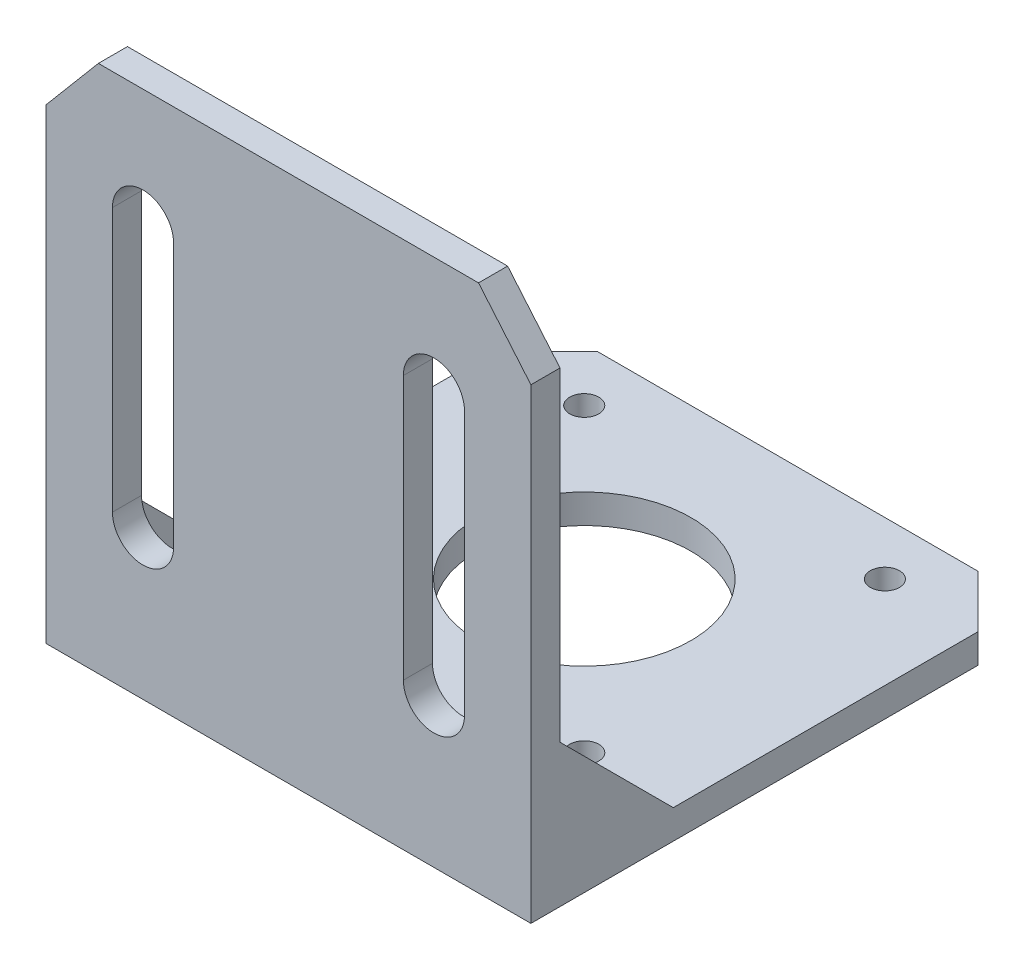
SolidWorks part; units mm, degrees
ref_plane "前视基准面" through (0, 0, 0) normal (0, 0, 1) x (1, 0, 0)
ref_plane "上视基准面" through (0, 0, 0) normal (0, 1, 0) x (1, 0, 0)
ref_plane "右视基准面" through (0, 0, 0) normal (1, 0, 0) x (0, 0, -1)
other "Configuration Table"
sketch "草图1" plane through (0, 0, 0) normal (0, 1, 0) x (1, 0, 0)
  line L0 (0, 32.108) -> (0, -16.3383) construction
  line L1 (-25, -23.05) -> (25, -23.05)
  line L2 (-25, -23.05) -> (-25, 23.05)
  line L3 (-19.6, 28.45) -> (19.6, 28.45)
  line L4 (25, -23.05) -> (25, 23.05)
  line L7 (-19.6, 28.45) -> (-25, 23.05)
  line L8 (19.6, 28.45) -> (25, 23.05)
  circle A1 centre (-15.5, 22.95) radius 1.5
  circle A2 centre (15.5, 22.95) radius 1.5
  circle A3 centre (-15.5, -8.05) radius 1.5
  circle A4 centre (15.5, -8.05) radius 1.5
  circle A5 centre (0, 7.45) radius 11
  point P0 (0, 0)
  dimension "D1" = 22
  dimension "D4" = 3
  dimension "D5" = 15.5
  dimension "D9" = 21
  dimension "D10" = 5.5
  dimension "D11" = 31
  dimension "D2" = 5.4
  dimension "D3" = 5.4
  dimension "D7" = 50
  dimension "D8" = 51.5
  dimension "D6" = 2
extrude "凸台-拉伸1" add sketch "草图1" along normal blind 3
ref_plane "基准面1" through (0, 0, 23.05) normal (0, 0, 1) x (1, 0, 0)
sketch "草图3" plane through (0, 0, 23.05) normal (0, 0, 1) x (1, 0, 0)
  line L0 (25, 0) -> (-25, 0)
  line L1 (-25, 0) -> (-25, 48.1)
  line L2 (-19.6, 54.5) -> (19.6, 54.5)
  line L3 (25, 48.1) -> (25, 0)
  line L4 (0, 60.86) -> (0, 19.2653) construction
  line L5 (-15, 42.35) -> (-15, 15.15) construction
  line L6 (-11.85, 42.35) -> (-11.85, 15.15)
  line L7 (-18.15, 42.35) -> (-18.15, 15.15)
  line L8 (15, 42.35) -> (15, 15.15) construction
  line L9 (11.85, 42.35) -> (11.85, 15.15)
  line L10 (18.15, 42.35) -> (18.15, 15.15)
  line L11 (-25, 48.1) -> (-19.6, 54.5)
  line L12 (25, 48.1) -> (19.6, 54.5)
  arc A0 (-11.85, 42.35) -> (-18.15, 42.35) centre (-15, 42.35) ccw
  arc A1 (-18.15, 15.15) -> (-11.85, 15.15) centre (-15, 15.15) ccw
  arc A2 (11.85, 42.35) -> (18.15, 42.35) centre (15, 42.35) cw
  arc A3 (18.15, 15.15) -> (11.85, 15.15) centre (15, 15.15) cw
  point P11 (-15, 28.75)
  point P16 (-15, 45.5)
  point P17 (-15, 12)
  point P20 (15, 28.75)
  dimension "D4" = 9
  dimension "D1" = 6.3
  dimension "D2" = 33.5
  dimension "D3" = 15
extrude "凸台-拉伸2" add sketch "草图3" against normal blind 3
sketch "草图4" plane through (-25, 0, 0) normal (-1, 0, 0) x (0, 0, 1)
  line L0 (20.05, 14.6802) -> (8.3698, 3)
  line L1 (20.05, 48.1) -> (20.05, 3) construction
  line L2 (-23.05, 3) -> (20.05, 3) construction
  dimension "D1" = 45
rib "筋2" sketch "草图4" sketch "草图4" thickness 3 extrusion direction parallel to sketch draft on no parameters "D1"=3
mirror "镜向1" about plane through (0, 0, 0) normal (1, 0, 0) of "筋2"
